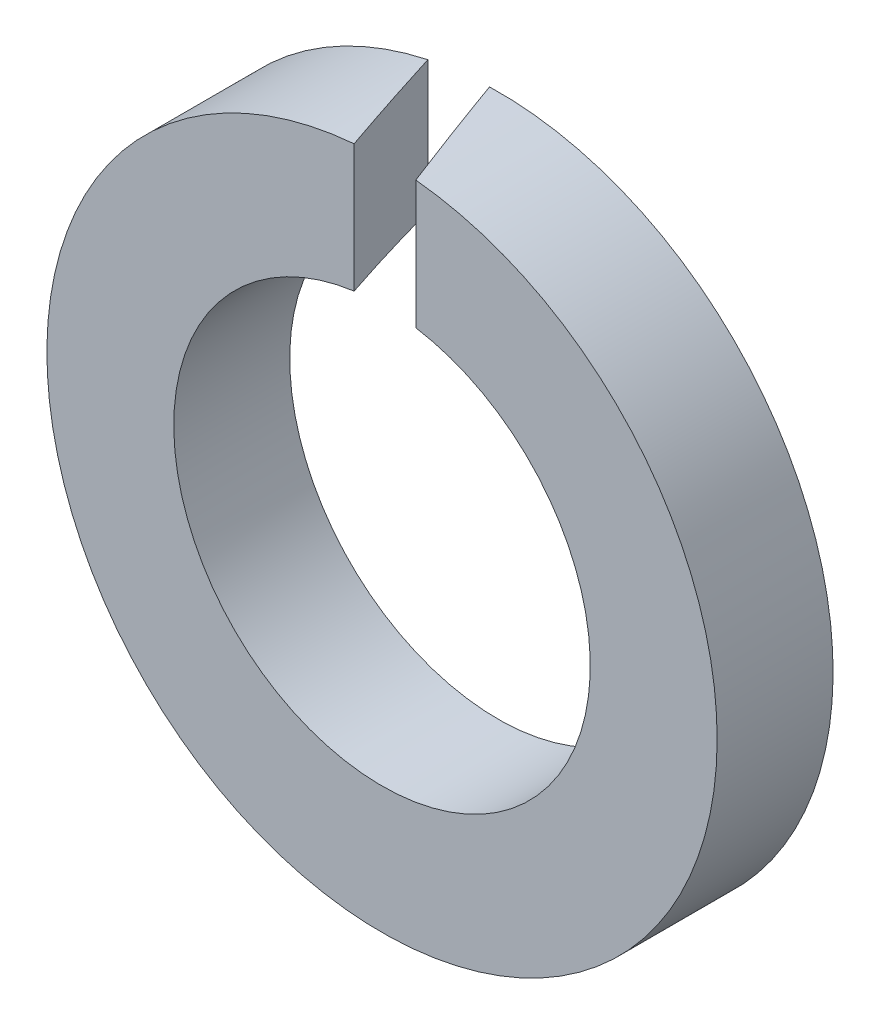
SolidWorks part; units mm, degrees
ref_plane "Front" through (0, 0, 0) normal (0, 0, 1) x (1, 0, 0)
ref_plane "Top" through (0, 0, 0) normal (0, 1, 0) x (1, 0, 0)
ref_plane "Right" through (0, 0, 0) normal (1, 0, 0) x (0, 0, -1)
other "Configuration Table"
sketch "Sketch1" plane through (0, 0, 0) normal (0, 0, 1) x (1, 0, 0)
  circle A0 centre (0, 0) radius 15.32
  circle A1 centre (0, 0) radius 9.52
  dimension "d" = 19.04
  dimension "b" = 5.8
extrude "Base-Extrude" add sketch "Sketch1" against normal blind 5.3
sketch "Sketch2" plane through (-3.0216, 0, -2.3453) normal (0, 1, 0) x (0, 0, -1)
  line L0 (0.7451, -1.8968) -> (-7.0218, -4.7237) construction
  line L1 (-2.3453, -1.7446) -> (2.9547, 0.1844)
  line L2 (2.9547, -18.3416) -> (2.9547, 12.2984) construction
  line L5 (-2.3453, -4.5647) -> (2.9547, -2.6356)
  line L6 (-2.3453, -1.7446) -> (-2.3453, -4.5647)
  line L7 (2.9547, 0.1844) -> (2.9547, -2.6356)
  line L8 (-2.3453, 6.4984) -> (-2.3453, -12.5416) construction
  line L10 (-2.3453, 12.2984) -> (-2.3453, -18.3416) construction
  dimension "D1" = 70
  dimension "m" = 2.65
  dimension "D3" = 2.4
extrude "Cut-Extrude1" cut sketch "Sketch2" along normal through all
